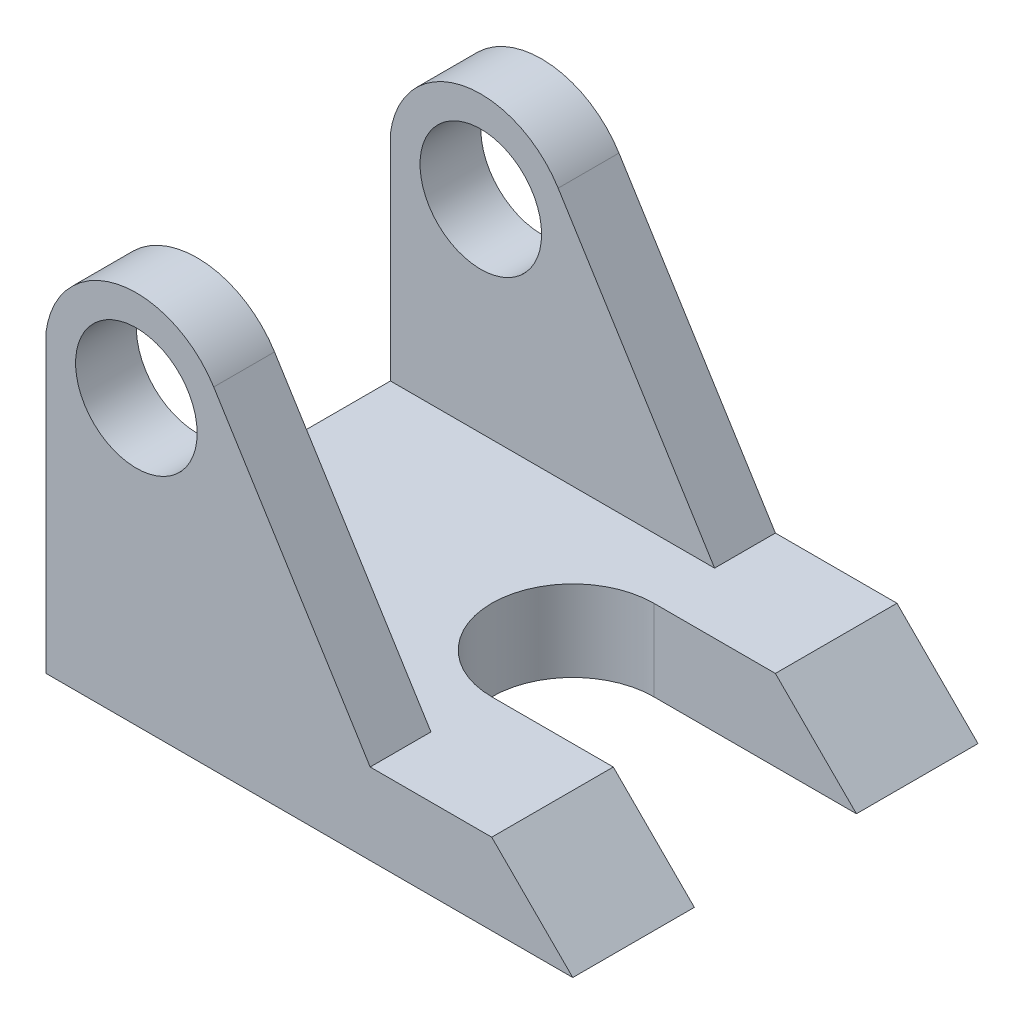
SolidWorks part; units mm, degrees
ref_plane "Front Plane" through (0, 0, 0) normal (0, 0, 1) x (1, 0, 0)
ref_plane "Top Plane" through (0, 0, 0) normal (0, 1, 0) x (1, 0, 0)
ref_plane "Right Plane" through (0, 0, 0) normal (1, 0, 0) x (0, 0, -1)
sketch "Sketch2" plane through (0, 0, 0) normal (0, 0, 1) x (1, 0, 0)
  line L0 (65, 0) -> (45, 20)
  line L1 (-65, 20) -> (45, 20)
  line L2 (-65, 20) -> (-65, 0)
  line L3 (-65, 0) -> (65, 0)
  dimension "D1" = 130
  dimension "D2" = 65
  dimension "D3" = 20
  dimension "D4" = 20
extrude "Boss-Extrude2" add sketch "Sketch2" against normal blind 100 contours L3 L0 L1 L2
sketch "Sketch3" plane through (0, 20, 0) normal (0, 1, 0) x (1, 0, 0)
  line L1 (65, 70) -> (15, 70)
  line L2 (65, 100) -> (65, 0) construction
  line L4 (15, 30) -> (65, 30)
  line L5 (65, 30) -> (65, 70)
  line L6 (-65, 100) -> (45, 100) construction
  arc A0 (15, 70) -> (15, 30) centre (15, 50) ccw
  dimension "D1" = 30
  dimension "D2" = 40
  dimension "D3" = 50
extrude "Cut-Extrude1" cut sketch "Sketch3" against normal through all contours A0 L4 L5 L1
sketch "Sketch4" plane through (0, 0, 0) normal (0, 0, 1) x (1, 0, 0)
  line L0 (-65, 20) -> (-65, 72.9858)
  line L1 (-65, 20) -> (45, 20) construction
  line L2 (-65, 20) -> (-65, 0) construction
  line L5 (15, 20) -> (-65, 20)
  line L6 (-23.6074, 81.9063) -> (15, 20)
  line L8 (-65, 0) -> (65, 0) construction
  arc A0 (-23.6074, 81.9063) -> (-65, 72.9858) centre (-42.699, 70) ccw
  point P7 (-41.6033, 70.7023)
  point P12 (0, 0)
  dimension "D3" = 70
  dimension "D1" = 22.5
  dimension "D2" = 30
extrude "Boss-Extrude6" add sketch "Sketch4" against normal blind 15 contours A0 L0 L5 L6
sketch "Sketch7" plane through (0, 0, -100) normal (0, 0, -1) x (-1, 0, 0)
sketch "Sketch9" plane through (0, 0, -100) normal (0, 0, -1) x (-1, 0, 0)
  line L0 (-15, 20) -> (23.6074, 81.9063)
  line L2 (65, 72.9858) -> (65, 20)
  line L3 (65, 20) -> (-15, 20)
  arc A0 (23.6074, 81.9063) -> (65, 72.9858) centre (42.699, 70) cw
extrude "Boss-Extrude8" add sketch "Sketch9" against normal blind 15
sketch "Sketch10" plane through (0, 0, 0) normal (0, 0, 1) x (1, 0, 0)
  circle A0 centre (-42.699, 70) radius 15
  dimension "D1" = 30
extrude "Cut-Extrude2" cut sketch "Sketch10" against normal through all
